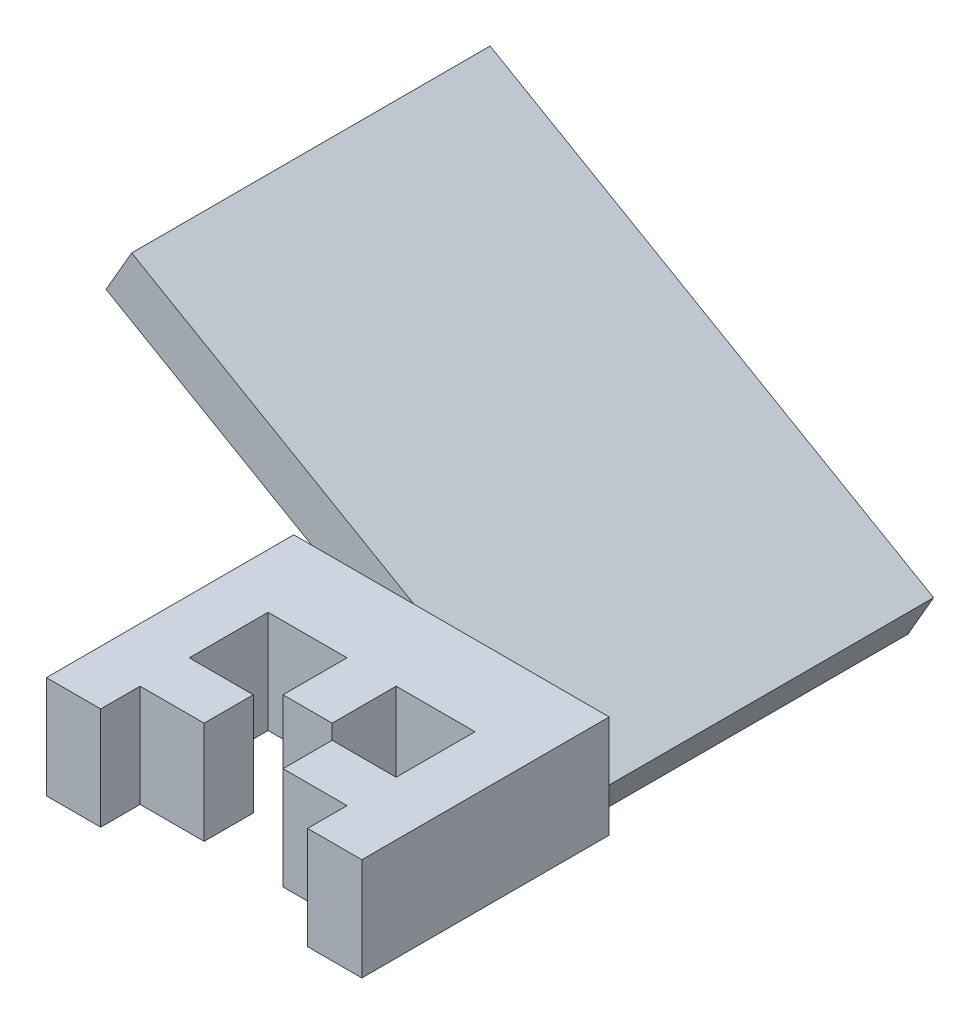
SolidWorks part; units mm, degrees
ref_plane "Plan de face" through (0, 0, 0) normal (0, 0, 1) x (1, 0, 0)
ref_plane "Plan de dessus" through (0, 0, 0) normal (0, 1, 0) x (1, 0, 0)
ref_plane "Plan de droite" through (0, 0, 0) normal (1, 0, 0) x (0, 0, -1)
sketch "Base" plane through (0, 0, 0) normal (0, 1, 0) x (1, 0, 0)
  line L0 (-3.85, -2.4) -> (-3.85, 2.4)
  line L1 (-3.85, 2.4) -> (-10.1, 2.4)
  line L2 (-10.1, 2.4) -> (-10.1, 10.1)
  line L3 (-10.1, 10.1) -> (-2.4, 10.1)
  line L4 (-2.4, 10.1) -> (-2.4, 3.85)
  line L5 (-2.4, 3.85) -> (2.4, 3.85)
  line L6 (0, -55) -> (0, 55) construction
  line L7 (2.4, 10.1) -> (2.4, 3.85)
  line L8 (10.1, 10.1) -> (2.4, 10.1)
  line L9 (10.1, 2.4) -> (10.1, 10.1)
  line L10 (3.85, 2.4) -> (10.1, 2.4)
  line L11 (3.85, -2.4) -> (3.85, 2.4)
  line L12 (-55, 0) -> (55, 0) construction
  line L13 (3.85, -2.4) -> (10.1, -2.4)
  line L14 (10.1, -2.4) -> (10.1, -6.25)
  line L20 (-10.1, -2.4) -> (-10.1, -6.25)
  line L21 (-3.85, -2.4) -> (-10.1, -2.4)
  line L23 (-15.4, 15.4) -> (15.4, 15.4)
  line L24 (-15.4, 15.4) -> (-15.4, -6.25)
  line L26 (15.4, 15.4) -> (15.4, -6.25)
  line L27 (-15.4, 15.4) -> (0, 0) construction
  line L28 (0, 0) -> (15.4, 15.4) construction
  line L29 (-10.1, -6.25) -> (-15.4, -6.25)
  line L30 (10.1, -6.25) -> (15.4, -6.25)
  line L31 (10.1, -10.1) -> (15.4, -15.4) construction
  point P2 (-3.85, 0)
  point P3 (0, 3.85)
  point P27 (0, 0)
  dimension "D1" = 4.8
  dimension "D2" = 4.8
  dimension "D3" = 6.25
  dimension "D4" = 7.7
  dimension "D5" = 30.8
extrude "Boss.-Extru.1" add sketch "Base" along normal mid plane 10
sketch "Esquisse14" plane through (0, -5, 0) normal (0, -1, 0) x (1, 0, 0)
  line L0 (15.4, 6.25) -> (15.4, -15.4) construction
  line L1 (-15.4, -15.4) -> (15.4, -15.4)
  line L2 (-15.4, -15.4) -> (-15.4, -17.9)
  line L3 (-15.4, -17.9) -> (15.4, -17.9)
  line L4 (15.4, -15.4) -> (15.4, -17.9)
  dimension "D1" = 2.5
extrude "Boss.-Extru.3" add sketch "Esquisse14" against normal up to vertex (10 mm away)
sketch "Esquisse16" plane through (0, 0, -17.9) normal (0, 0, -1) x (-1, 0, 0)
  line L0 (31.2263, 20.9201) -> (33.7263, 16.59)
  line L1 (31.2263, 20.9201) -> (-12.075, -4.0799)
  line L2 (33.7263, 16.59) -> (-9.575, -8.41)
  line L3 (-12.075, -4.0799) -> (-9.575, -8.41)
  line L4 (15.4, -5) -> (-15.4, -5) construction
  line L5 (-15.4, 5) -> (-15.4, -5) construction
  point P0 (0, 0)
  dimension "D1" = 30
  dimension "D2" = 5
  dimension "D3" = 50
  dimension "D4" = 3.325
  dimension "D5" = 3.41
extrude "Boss.-Extru.5" add sketch "Esquisse16" along normal blind 35
